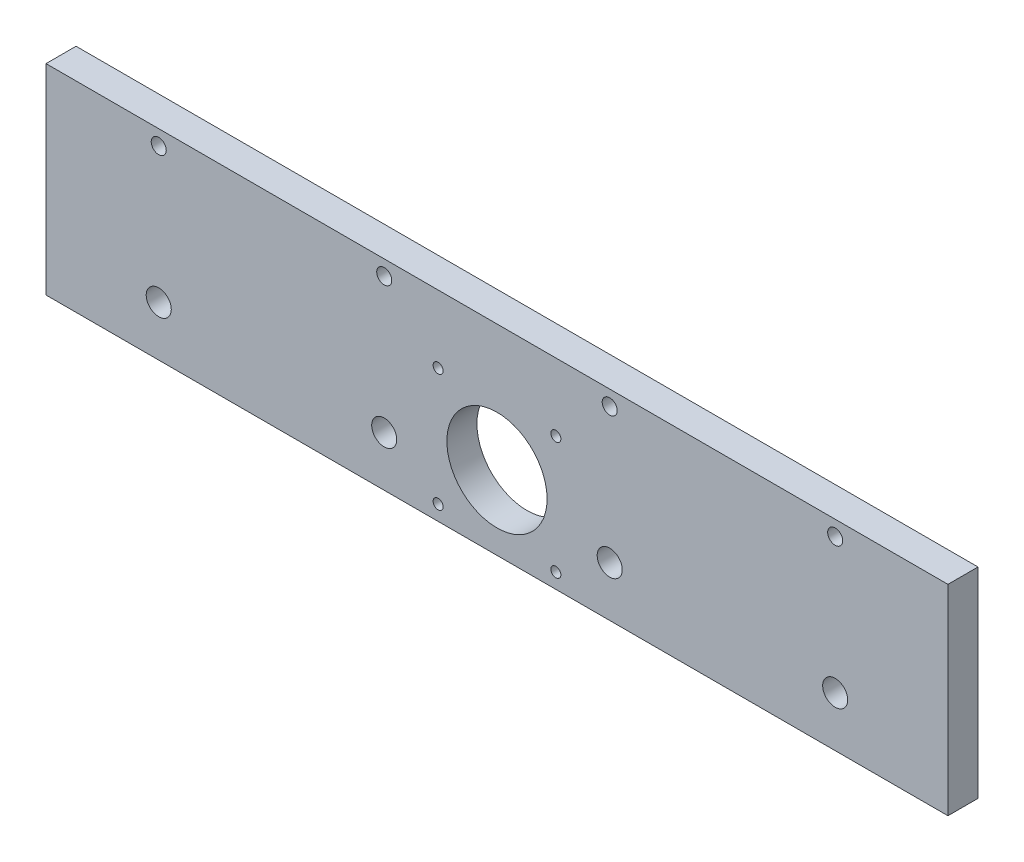
SolidWorks part; units mm, degrees
material "Beech"
ref_plane "Front Plane" through (0, 0, 0) normal (0, 0, 1) x (1, 0, 0)
ref_plane "Top Plane" through (0, 0, 0) normal (0, 1, 0) x (1, 0, 0)
ref_plane "Right Plane" through (0, 0, 0) normal (1, 0, 0) x (0, 0, -1)
sketch "Sketch1" plane through (0, 0, 0) normal (0, 0, 1) x (1, 0, 0)
  line L1 (-180, -40) -> (180, -40)
  line L2 (-180, -40) -> (-180, 40)
  line L3 (-180, 40) -> (180, 40)
  line L4 (180, -40) -> (180, 40)
  line L5 (-180, -40) -> (180, 40) construction
  line L6 (-180, 40) -> (180, -40) construction
  point P0 (0, 0)
extrude "Boss-Extrude1" add sketch "Sketch1" along normal blind 12
sketch "Sketch2" plane through (0, 0, 12) normal (0, 0, 1) x (1, 0, 0)
  line L0 (180, -40) -> (180, 40) construction
  line L1 (180, 40) -> (-180, 40) construction
  line L2 (-180, -40) -> (180, -40) construction
  circle A0 centre (135, 34) radius 3
  circle A1 centre (135, -20) radius 5
  dimension "D1" = 6
  dimension "D2" = 45
  dimension "D3" = 6
  dimension "D4" = 10
  dimension "D5" = 20
extrude "Cut-Extrude1" cut sketch "Sketch2" against normal up to next
pattern_linear "LPattern1" count 4 spacing 90 along (-1, 0, 0) of "Cut-Extrude1"
sketch "Sketch3" plane through (0, 0, 12) normal (0, 0, 1) x (1, 0, 0)
  line L0 (-180, -40) -> (180, -40) construction
  circle A0 centre (0, -10.5) radius 20
  dimension "D1" = 40
  dimension "D2" = 29.5
extrude "Cut-Extrude2" cut sketch "Sketch3" against normal up to next
sketch "Sketch4" plane through (0, 0, 12) normal (0, 0, 1) x (1, 0, 0)
  line L0 (0, 17.4189) -> (0, -17.4926) construction
  line L1 (-17.6695, 0) -> (16.7711, 0) construction
  circle A0 centre (-23.5, 13) radius 2
  circle A1 centre (0, -10.5) radius 20 construction
  circle A2 centre (-23.5, -34) radius 2
  dimension "D1" = 4
  dimension "D2" = 23.5
  dimension "D3" = 23.5
  dimension "D4" = 4
  dimension "D5" = 23.5
  dimension "D6" = 23.5
extrude "Cut-Extrude3" cut sketch "Sketch4" against normal up to next
mirror "Mirror2" about plane through (0, 0, 0) normal (1, 0, 0) of "Cut-Extrude3"
